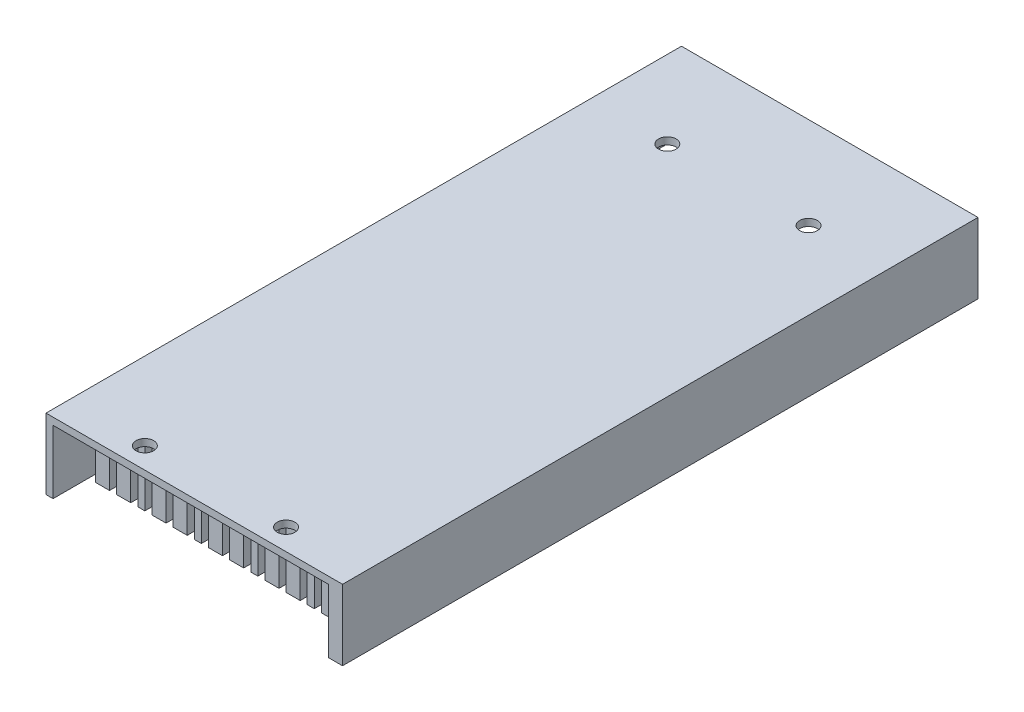
SolidWorks part; units mm, degrees
ref_plane "Plan de face" through (0, 0, 0) normal (0, 0, 1) x (1, 0, 0)
ref_plane "Plan de dessus" through (0, 0, 0) normal (0, 1, 0) x (1, 0, 0)
ref_plane "Plan de droite" through (0, 0, 0) normal (1, 0, 0) x (0, 0, -1)
sketch "Esquisse1" plane through (0, 0, 0) normal (0, 0, 1) x (1, 0, 0)
  line L0 (0, 0) -> (-2, 0)
  line L1 (-2, 0) -> (-2, 9)
  line L2 (-2, 9) -> (-3, 9)
  line L3 (-3, 9) -> (-3, 0)
  line L4 (-3, 0) -> (-5, 0)
  line L5 (-5, 0) -> (-5, 9)
  line L6 (-5, 9) -> (-6, 9)
  line L7 (-6, 9) -> (-6, 0)
  line L8 (-6, 0) -> (-8, 0)
  line L9 (-8, 0) -> (-8, 9)
  line L10 (0, 0) -> (-42, 0) construction
  line L11 (-8, 9) -> (-9, 9)
  line L12 (-9, 9) -> (-9, 0)
  line L13 (-10, 0) -> (-10, 9)
  line L14 (-10, 9) -> (-11, 9)
  line L15 (-11, 9) -> (-11, 0)
  line L16 (-13, 0) -> (-13, 9)
  line L17 (-11, 0) -> (-13, 0)
  line L18 (-14, 0) -> (-16, 0)
  line L19 (-14, 9) -> (-14, 0)
  line L20 (-16, 0) -> (-16, 9)
  line L21 (-17, 9) -> (-17, 0)
  line L22 (-16, 9) -> (-17, 9)
  line L23 (-13, 9) -> (-14, 9)
  line L24 (-18, 0) -> (-18, 9)
  line L25 (-18, 9) -> (-19, 9)
  line L26 (-19, 9) -> (-19, 0)
  line L27 (-21, 0) -> (-21, 9)
  line L28 (-19, 0) -> (-21, 0)
  line L29 (-22, 0) -> (-24, 0)
  line L30 (-22, 9) -> (-22, 0)
  line L31 (-24, 0) -> (-24, 9)
  line L32 (-25, 9) -> (-25, 0)
  line L33 (-24, 9) -> (-25, 9)
  line L34 (-21, 9) -> (-22, 9)
  line L35 (-26, 0) -> (-26, 9)
  line L36 (-26, 9) -> (-27, 9)
  line L37 (-27, 9) -> (-27, 0)
  line L38 (-29, 0) -> (-29, 9)
  line L39 (-27, 0) -> (-29, 0)
  line L40 (-30, 0) -> (-32, 0)
  line L41 (-30, 9) -> (-30, 0)
  line L42 (-32, 0) -> (-32, 9)
  line L43 (-33, 9) -> (-33, 0)
  line L44 (-32, 9) -> (-33, 9)
  line L45 (-29, 9) -> (-30, 9)
  line L46 (-34, 0) -> (-34, 9)
  line L47 (-34, 9) -> (-35, 9)
  line L48 (-35, 9) -> (-35, 0)
  line L49 (-37, 0) -> (-37, 9)
  line L50 (-35, 0) -> (-37, 0)
  line L51 (-38, 0) -> (-40, 0)
  line L52 (-38, 9) -> (-38, 0)
  line L53 (-40, 0) -> (-40, 9)
  line L54 (-41, 9) -> (-41, 0)
  line L55 (-40, 9) -> (-41, 9)
  line L56 (-37, 9) -> (-38, 9)
  line L57 (-17, 0) -> (-18, 0)
  line L58 (-9, 0) -> (-10, 0)
  line L59 (-25, 0) -> (-26, 0)
  line L60 (-33, 0) -> (-34, 0)
  line L61 (-41, 0) -> (-42, 0)
  line L62 (-42, 0) -> (-42, 10)
  line L63 (-42, 10) -> (0, 10)
  line L64 (0, 10) -> (0, 0)
  point P14 (-2.5, 9)
  dimension "D1" = 42
  dimension "D2" = 2
  dimension "D3" = 2
  dimension "D4" = 1
  dimension "D5" = 1
  dimension "D6" = 2
  dimension "D7" = 1
  dimension "D8" = 9
  dimension "D10" = 1
  dimension "D11" = 1
  dimension "D9" = 5
extrude "Boss.-Extru.1" add sketch "Esquisse1" along normal blind 90
sketch "Esquisse3" plane through (0, 0, 90) normal (0, 0, 1) x (1, 0, 0)
  line L1 (-41, 0) -> (-2, 0)
  line L2 (-41, 0) -> (-41, 9)
  line L3 (-41, 9) -> (-2, 9)
  line L4 (-2, 0) -> (-2, 9)
extrude "Enlèv. mat.-Extru.1" cut sketch "Esquisse3" against normal blind 5
sketch "Esquisse4" plane through (0, 10, 0) normal (0, 1, 0) x (1, 0, 0)
  line L0 (-42, -87) -> (0, -87) construction
  line L1 (-42, -90) -> (-42, 0) construction
  line L2 (0, -90) -> (0, 0) construction
  line L3 (0, -90) -> (-42, -90) construction
  line L4 (-42, -10) -> (0, -10) construction
  line L5 (0, 0) -> (-42, 0) construction
  line L6 (-5.4592, -10) -> (-5.4592, -90) construction
  line L7 (-5.4592, -50) -> (-42, -50) construction
  circle A0 centre (-31, -87) radius 1.25
  circle A1 centre (-11, -87) radius 1.25
  circle A2 centre (-11, -13) radius 1.25
  circle A3 centre (-31, -13) radius 1.25
  point P24 (0, 0)
  dimension "D2" = 2.5
  dimension "D3" = 11
  dimension "D5" = 11
  dimension "D1" = 3
  dimension "D4" = 2
  dimension "D6" = 10
extrude "Enlèv. mat.-Extru.2" cut sketch "Esquisse4" against normal blind 5
sketch "Esquisse5" plane through (0, 0, 0) normal (0, 0, -1) x (-1, 0, 0)
  line L1 (2, 0) -> (41, 0)
  line L2 (2, 0) -> (2, 9)
  line L3 (2, 9) -> (41, 9)
  line L4 (41, 0) -> (41, 9)
extrude "Enlèv. mat.-Extru.3" cut sketch "Esquisse5" against normal blind 16
